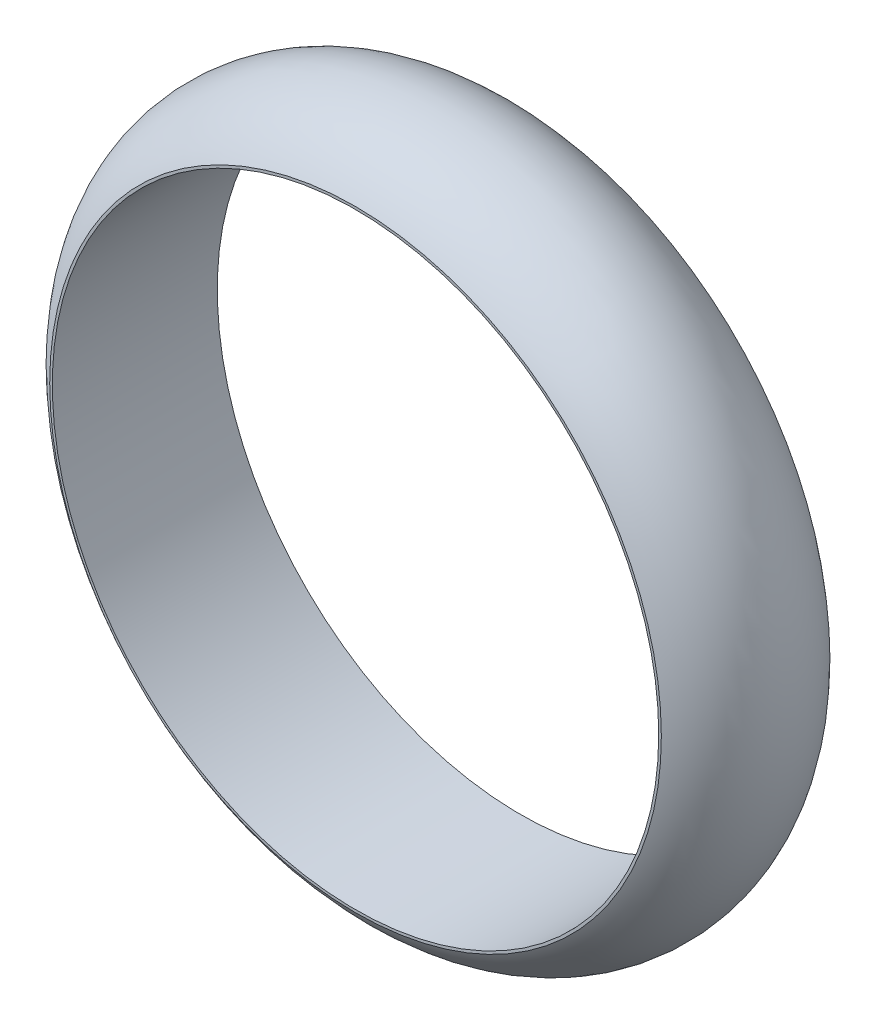
SolidWorks part; units mm, degrees
material "聚亚安酯(11671)"
ref_plane "前视基准面" through (0, 0, 0) normal (0, 0, 1) x (1, 0, 0)
ref_plane "上视基准面" through (0, 0, 0) normal (0, 1, 0) x (1, 0, 0)
ref_plane "右视基准面" through (0, 0, 0) normal (1, 0, 0) x (0, 0, -1)
sketch "草图1" plane through (0, 0, 0) normal (0, 0, 1) x (1, 0, 0)
  circle A0 centre (0, 0) radius 62.5
  circle A1 centre (0, 0) radius 72.5
  dimension "D1" = 125
  dimension "D2" = 145
extrude "凸台-拉伸1" add sketch "草图1" along normal blind 34
sketch "草图3" plane through (0, 0, 0) normal (1, 0, 0) x (0, 0, -1)
  line L0 (-34, 72.5) -> (-34, -72.5) construction
  line L1 (0, -72.5) -> (0, 72.5) construction
  line L2 (-34, 63.0357) -> (-34, 72.5)
  line L3 (-34, 72.5) -> (0, 72.5)
  line L4 (0, 72.5) -> (0, 63.0357)
  line L5 (-34, 52.5) -> (0, 52.5) construction
  line L6 (0, 0) -> (-34, 0) construction
  arc A0 (-34, 63.0357) -> (0, 63.0357) centre (-17, 52.5) cw
  point P7 (-17, 52.5)
  dimension "D2" = 20
revolve "切除-旋转1" cut sketch "草图3" angle 360 about L6
